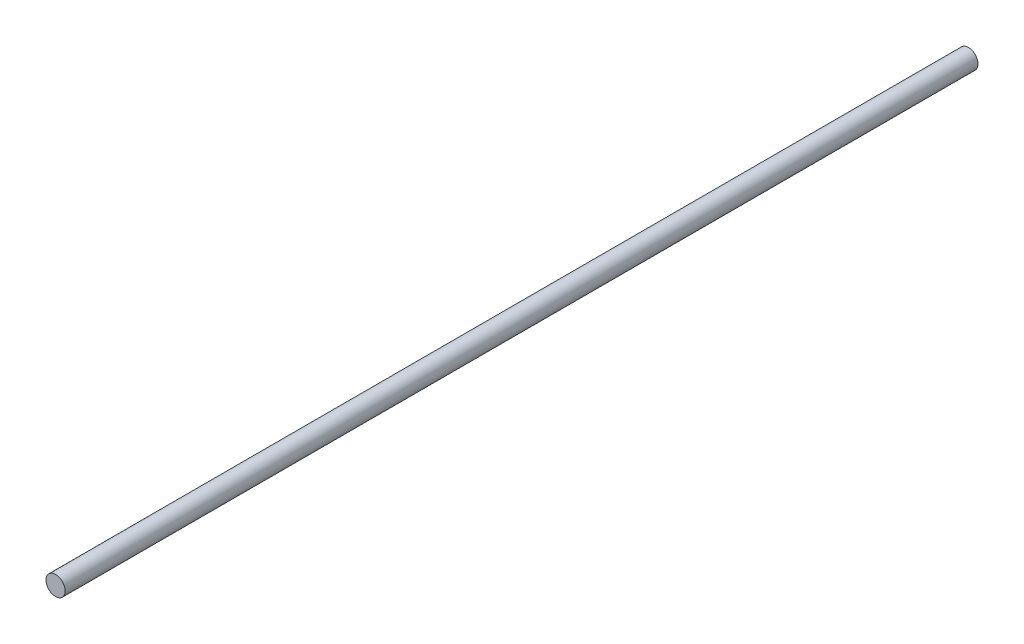
SolidWorks part; units mm, degrees
ref_plane "Front" through (0, 0, 0) normal (0, 0, 1) x (1, 0, 0)
ref_plane "Top" through (0, 0, 0) normal (0, 1, 0) x (1, 0, 0)
ref_plane "Right" through (0, 0, 0) normal (1, 0, 0) x (0, 0, -1)
sketch "Sketch1" plane through (0, 0, 0) normal (0, 0, 1) x (1, 0, 0)
  circle A0 centre (-1.2403, -1.1309) radius 3.15
  dimension "D1" = 6.3
extrude "Boss-Extrude1" add sketch "Sketch1" along normal blind 300
